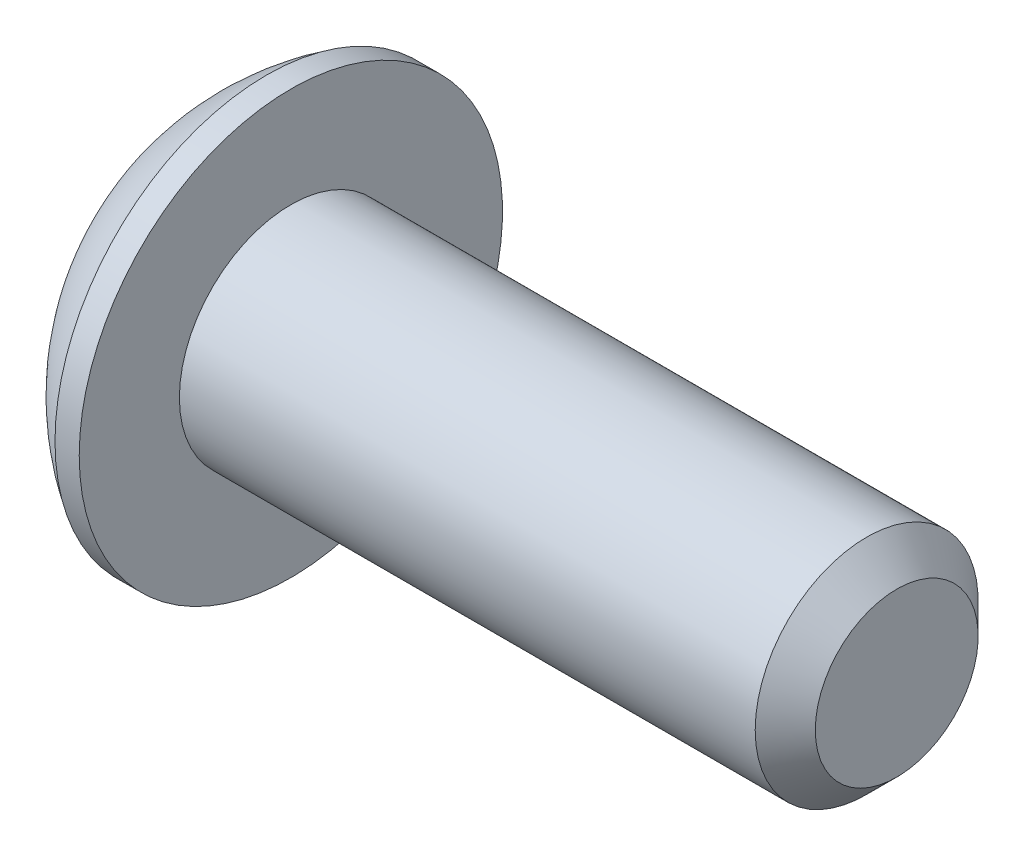
SolidWorks part; units mm, degrees
material "Alloy Steel"
ref_plane "Plane1" through (0, 0, 0) normal (0, 0, 1) x (1, 0, 0)
ref_plane "Plane2" through (0, 0, 0) normal (0, 1, 0) x (1, 0, 0)
ref_plane "Plane3" through (0, 0, 0) normal (1, 0, 0) x (0, 0, -1)
revolve "BaseBody" add sketch "BodySke" angle 360 about L4
sketch "BodySke" plane through (0, 0, 0) normal (0, 0, 1) x (1, 0, 0)
  line L0 (11.3792, 0) -> (11.3792, 1.2802)
  line L1 (10.9068, 1.7526) -> (1.8542, 1.7526)
  line L2 (1.8542, 1.7526) -> (1.8542, 3.3274)
  line L3 (1.8542, 3.3274) -> (1.4732, 3.3274)
  line L4 (0, 0) -> (101.6, 0) construction
  line L5 (1.8542, -3.3274) -> (1.4732, -3.3274) construction
  line L6 (55.6768, -1.7526) -> (1.8542, -1.7526) construction
  line L7 (11.3792, 0) -> (0, 0)
  line L8 (0, 1.6637) -> (0, -1.6637) construction
  line L9 (0, 0) -> (0, 1.6637)
  line L10 (11.3792, 1.2802) -> (10.9068, 1.7526)
  line L11 (11.3792, -1.2802) -> (10.9068, -1.7526) construction
  line L12 (2.6467, 9.525) -> (2.6467, -1.7526) construction
  line L13 (1.8542, 9.525) -> (1.8542, -1.7526) construction
  arc A1 (0, 1.6637) -> (1.4732, 3.3274) centre (3.5549, 0) cw
  dimension "D1" = 3.3274
  dimension "Diameter" = 3.5052
  dimension "Length" = 9.525
  dimension "Head_dia" = 6.6548
  dimension "Head_ht" = 1.8542
  dimension "Head_side_ht" = 0.381
  dimension "Minor_dia" = 2.5603
  dimension "Body_ch_ang" = 45
  dimension "Advance" = 0.7925
  dimension "Thread_nom" = 9.525
cosmetic thread "ThreadCosmetic" parameters "Thread_length"=8.7325, "Thread_minor"=2.5603
sketch "Sketch2" plane through (0, 0, 0) normal (0, 0, 1) x (1, 0, 0)
  line L0 (0, 0.9906) -> (1.1176, 0.9906)
  line L1 (1.1176, 0.9906) -> (1.6895, 0)
  line L3 (1.6895, 0) -> (0, 0)
  line L4 (0, 0) -> (0, 0.9906)
  line L5 (0, -0.9906) -> (1.1176, -0.9906) construction
  line L6 (0, 0) -> (47.625, 0) construction
  dimension "D2" = 60
  dimension "PreBroach_depth" = 1.1176
  dimension "PreBroach_dia" = 1.9812
revolve "PreBroach" cut sketch "Sketch2" angle 360 about L6
sketch "Sketch3" plane through (0, 0, 0) normal (1, 0, 0) x (0, 0, -1)
  line L0 (-0.9906, -0.5719) -> (-0.9906, 0.5719)
  line L1 (-0.9906, 0.5719) -> (0, 1.1438)
  line L2 (0, 1.1438) -> (0.9906, 0.5719)
  line L3 (0.9906, 0.5719) -> (0.9906, -0.5719)
  line L4 (0.9906, -0.5719) -> (0, -1.1438)
  line L5 (0, -1.1438) -> (-0.9906, -0.5719)
  dimension "D1" = 0.9906
  dimension "D2" = 0.9906
  dimension "D3" = 1.9812
  dimension "Hex_size" = 1.9812
extrude "Hex" cut sketch "Sketch3" along normal blind 1.1176
sketch "Sketch4" plane through (0, 9.525, 0) normal (1, 0, 0) x (0, 0, -1)
  line L0 (0, -9.525) -> (1.2446, -9.525)
  line L1 (0, -9.525) -> (6.1484, -5.9752) construction
  line L2 (0, -9.525) -> (0.6223, -8.4471)
  line L3 (1.0085, -9.2654) -> (1.19, -9.1606)
  line L4 (0.7291, -8.7814) -> (0.9106, -8.6766)
  arc A0 (1.0085, -9.2654) -> (0.7291, -8.7814) centre (0, -9.525) ccw
  arc A1 (1.2446, -9.525) -> (1.19, -9.1606) centre (0, -9.525) ccw
  arc A2 (0.6223, -8.4471) -> (0.9106, -8.6766) centre (0, -9.525) cw
  dimension "D1" = 30
  dimension "Spline_n_dim" = 2.0828
  dimension "Spline_m_dim" = 2.4892
  dimension "D2" = 60
  dimension "D3" = 0.2794
  dimension "Spline_p_dim" = 0.5588
extrude "Spline" [suppressed] cut sketch "Sketch4" along normal blind 1.1176
pattern_circular "CirPattern1" [suppressed] count 6 every 60 about axis through (0, 0, 0) along (1, 0, 0)
sketch "ThdSchSke" plane through (0, 0, 0) normal (0, 0, 1) x (1, 0, 0)
  line L0 (2.6467, -1.2802) -> (2.3159, -1.7526)
  line L1 (2.6467, -1.2802) -> (2.9775, -1.7526)
  line L2 (2.9775, -1.7526) -> (2.9775, -2.1908)
  line L3 (-3.175, 0) -> (5.1513, 0) construction
  line L5 (2.9775, -2.1908) -> (2.3159, -2.1908)
  line L6 (2.3159, -2.1908) -> (2.3159, -1.7526)
  dimension "Thread_minor" = 2.5603
  dimension "Diameter" = 3.5052
  dimension "Start" = 2.6467
  dimension "SideAngle" = 55
  dimension "VeeAngle" = 70
  dimension "Overcut" = 4.3815
revolve "ThreadSchematic" [suppressed] cut sketch "ThdSchSke" angle 360 about L3
pattern_linear "ThdSchPat" [suppressed]
equation "\"D1@BodySke\" = \"Head_dia@BodySke\" * .5"
equation "\"Thread_minor@ThreadCosmetic\" = \"Minor_dia@BodySke\""
equation "\"D1@Sketch3\" = \"Hex_size@Sketch3\" / 2"
equation "\"D2@Sketch3\" = \"D1@Sketch3\""
equation "\"D3@Sketch3\" = \"Hex_size@Sketch3\""
equation "\"D3@Sketch4\" = \"Spline_p_dim@Sketch4\" / 2"
equation "\"D1@Sketch4\" = \"D2@Sketch4\" / 2"
equation "\"Thread_length@ThreadCosmetic\" = ((sgn( (\"Length@BodySke\" - \"Advance@BodySke\" ) - \"Thread_nom@BodySke\" )-1)*( (\"Length@BodySke\" - \"Advance@BodySke\" ) - \"Thread_nom@BodySke\" ))/-2+ \"Thread_nom@BodySke\""
equation "\"Thread_minor@ThdSchSke\" = \"Minor_dia@BodySke\""
equation "\"Diameter@ThdSchSke\" = \"Diameter@BodySke\""
equation "\"Overcut@ThdSchSke\" = \"Diameter@BodySke\" * 1.25"
equation "\"Start@ThdSchSke\" = \"Head_ht@BodySke\" + \"Length@BodySke\" - \"Thread_length@ThreadCosmetic\"  '---Non-countersunk---"
equation "\"Num_threads@ThdSchPat\" = int( \"Thread_length@ThreadCosmetic\" / \"Advance@BodySke\" + 0.999 )  + 1"
equation "\"Advance@ThdSchPat\" = \"Thread_length@ThreadCosmetic\" /  (\"Num_threads@ThdSchPat\" - 1) 'relax it"
equation "\"Num_threads@ThdSchPat\" = \"Num_threads@ThdSchPat\" - sgn( \"Num_threads@ThdSchPat\" - 1) '---chamfered tips only---"
